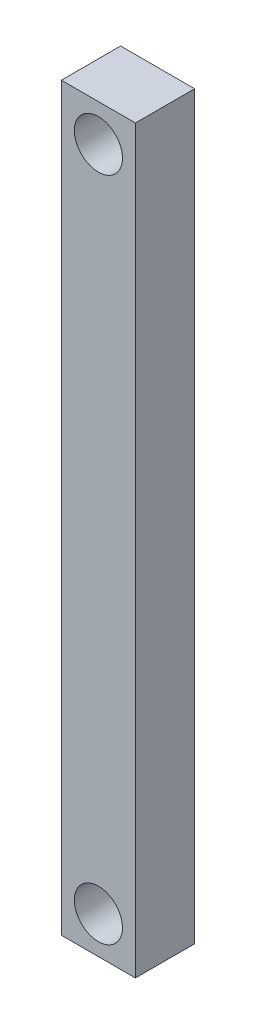
SolidWorks part; units mm, degrees
ref_plane "Front Plane" through (0, 0, 0) normal (0, 0, 1) x (1, 0, 0)
ref_plane "Top Plane" through (0, 0, 0) normal (0, 1, 0) x (1, 0, 0)
ref_plane "Right Plane" through (0, 0, 0) normal (1, 0, 0) x (0, 0, -1)
sketch "Sketch1" plane through (0, 0, 0) normal (0, 0, 1) x (1, 0, 0)
  line L0 (-2.5, 0) -> (2.5, 0) construction
  line L1 (-2.5, -25) -> (2.5, -25)
  line L2 (-2.5, -25) -> (-2.5, 25)
  line L3 (-2.5, 25) -> (2.5, 25)
  line L4 (2.5, -25) -> (2.5, 25)
  line L5 (-2.5, -25) -> (2.5, 25) construction
  line L6 (-2.5, 25) -> (2.5, -25) construction
  line L7 (0, 25) -> (0, 22.5) construction
  circle A0 centre (0, 22.5) radius 1.625
  circle A1 centre (0, -22.5) radius 1.625
  point P0 (0, 0)
  point P13 (0, 0)
  point P14 (0, 0)
  dimension "D3" = 3.25
  dimension "D1" = 5
  dimension "D2" = 50
  dimension "D4" = 2.5
extrude "Boss-Extrude1" add sketch "Sketch1" along normal blind 4 contours A0
equation "\"D4@Sketch1\"=\"D1@Sketch1\"/2"
